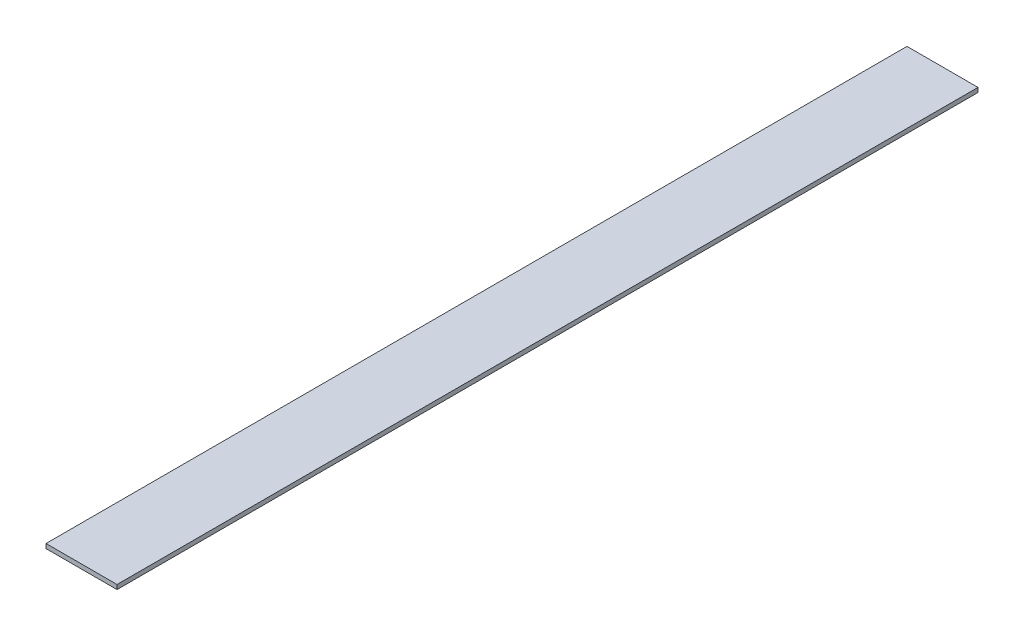
SolidWorks part; units mm, degrees
ref_plane "Front Plane" through (0, 0, 0) normal (0, 0, 1) x (1, 0, 0)
ref_plane "Top Plane" through (0, 0, 0) normal (0, 1, 0) x (1, 0, 0)
ref_plane "Right Plane" through (0, 0, 0) normal (1, 0, 0) x (0, 0, -1)
sketch "Sketch1" plane through (0, 0, 0) normal (0, 1, 0) x (1, 0, 0)
  line L1 (-25.4, -307.975) -> (25.4, -307.975)
  line L2 (-25.4, -307.975) -> (-25.4, 307.975)
  line L3 (-25.4, 307.975) -> (25.4, 307.975)
  line L4 (25.4, -307.975) -> (25.4, 307.975)
  line L5 (-25.4, -307.975) -> (25.4, 307.975) construction
  line L6 (-25.4, 307.975) -> (25.4, -307.975) construction
  point P0 (0, 0)
  dimension "D1" = 50.8
  dimension "D2" = 615.95
extrude "Boss-Extrude1" add sketch "Sketch1" along normal blind 3.175
